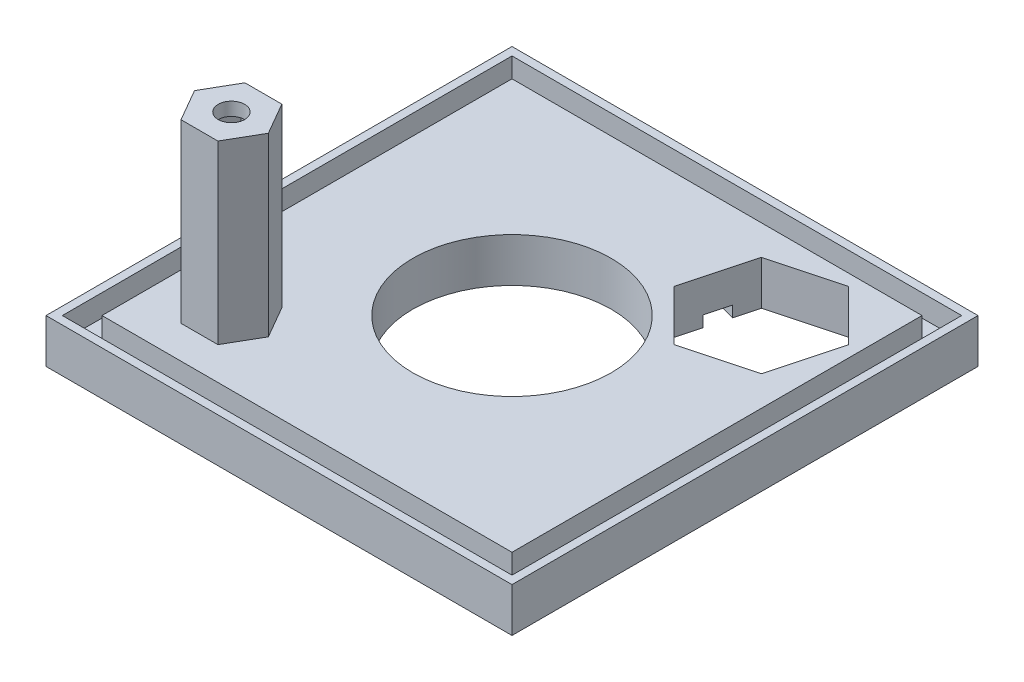
SolidWorks part; units mm, degrees
ref_plane "Front Plane" through (0, 0, 0) normal (0, 0, 1) x (1, 0, 0)
ref_plane "Top Plane" through (0, 0, 0) normal (0, 1, 0) x (1, 0, 0)
ref_plane "Right Plane" through (0, 0, 0) normal (1, 0, 0) x (0, 0, -1)
sketch "Sketch1" plane through (0, 0, 0) normal (0, 1, 0) x (1, 0, 0)
  line L1 (-52.85, -52.85) -> (52.85, -52.85)
  line L2 (-52.85, -52.85) -> (-52.85, 52.85)
  line L3 (-52.85, 52.85) -> (52.85, 52.85)
  line L4 (52.85, -52.85) -> (52.85, 52.85)
  line L5 (-52.85, -52.85) -> (52.85, 52.85) construction
  line L6 (-52.85, 52.85) -> (52.85, -52.85) construction
  line L11 (-82.2142, -82.2142) -> (73.2478, 73.2478) construction
  line L12 (-76.9859, 78.469) -> (76.9859, -78.469) construction
  circle A1 centre (0, 0) radius 22.5
  dimension "D1" = 105.7
  dimension "D2" = 45
  dimension "D3" = 105.7
extrude "Boss-Extrude1" add sketch "Sketch1" along normal blind 10
sketch "Sketch3" plane through (0, 10, 0) normal (0, 1, 0) x (1, 0, 0)
  line L1 (-51, -51) -> (51, -51)
  line L2 (-51, -51) -> (-51, 51)
  line L3 (-51, 51) -> (51, 51)
  line L4 (51, -51) -> (51, 51)
  line L5 (-51, -51) -> (51, 51) construction
  line L6 (-51, 51) -> (51, -51) construction
  line L7 (-46.5, -46.5) -> (46.5, -46.5)
  line L8 (-46.5, -46.5) -> (-46.5, 46.5)
  line L9 (-46.5, 46.5) -> (46.5, 46.5)
  line L10 (46.5, -46.5) -> (46.5, 46.5)
  line L11 (-46.5, -46.5) -> (46.5, 46.5) construction
  line L12 (-46.5, 46.5) -> (46.5, -46.5) construction
  point P0 (0, 0)
  point P2 (0, 0)
  dimension "D4" = 102
  dimension "D6" = 93
extrude "Cut-Extrude1" cut sketch "Sketch3" against normal blind 5
sketch "Sketch4" plane through (0, 10, 0) normal (0, 1, 0) x (1, 0, 0)
  line L0 (0, 0) -> (28.2843, 28.2843) construction
  line L1 (0, 0) -> (46.5, 0) construction
  line L2 (46.5, -46.5) -> (46.5, 46.5) construction
  circle A0 centre (28.2843, 28.2843) radius 10.375
  dimension "D1" = 20.75
  dimension "D2" = 40
  dimension "D3" = 45
sketch "Sketch8" plane through (0, 10, 0) normal (0, -1, 0) x (1, 0, 0)
  line L0 (0, 0) -> (-31.8198, 31.8198) construction
  line L1 (0, 0) -> (-22.5, 0) construction
  circle A0 centre (-31.8198, 31.8198) radius 3
  circle A2 centre (0, 0) radius 22.5 construction
  dimension "D1" = 6
  dimension "D2" = 45
  dimension "D3" = 45
extrude "Cut-Extrude5" cut sketch "Sketch8" along normal through all
sketch "Sketch9" plane through (0, 10, 0) normal (0, -1, 0) x (1, 0, 0)
  line L1 (-23.4482, 31.8198) -> (-27.634, 39.0698)
  line L2 (-27.634, 39.0698) -> (-36.0056, 39.0698)
  line L3 (-36.0056, 39.0698) -> (-40.1914, 31.8198)
  line L4 (-40.1914, 31.8198) -> (-36.0056, 24.5698)
  line L5 (-36.0056, 24.5698) -> (-27.634, 24.5698)
  line L6 (-27.634, 24.5698) -> (-23.4482, 31.8198)
  circle A0 centre (-31.8198, 31.8198) radius 7 construction
  circle A2 centre (-31.8198, 31.8198) radius 3 construction
  circle A3 centre (-31.8198, 31.8198) radius 3
  circle A4 centre (-31.8198, 31.8198) radius 7.25 construction
  dimension "D1" = 14
  dimension "D2" = 14.5
extrude "Cut-Extrude7" cut sketch "Sketch4" against normal through all
sketch "Sketch12" plane through (0, 0, 0) normal (0, -1, 0) x (1, 0, 0)
  line L0 (28.2843, -28.2843) -> (1.5232, -28.2843) construction
  line L1 (43.8992, -32.4683) -> (39.7152, -16.8533)
  line L2 (39.7152, -16.8533) -> (24.1003, -12.6693)
  line L3 (24.1003, -12.6693) -> (12.6693, -24.1003)
  line L4 (12.6693, -24.1003) -> (16.8533, -39.7152)
  line L5 (16.8533, -39.7152) -> (32.4683, -43.8992)
  line L6 (32.4683, -43.8992) -> (43.8992, -32.4683)
  circle A0 centre (28.2843, -28.2843) radius 14 construction
  dimension "D1" = 28
  dimension "D2" = 45
sketch "Sketch15" plane through (0, 0, 0) normal (0, -1, 0) x (1, 0, 0)
  line L1 (-25.238, 31.8198) -> (-28.5289, 37.5198)
  line L2 (-28.5289, 37.5198) -> (-35.1107, 37.5198)
  line L3 (-35.1107, 37.5198) -> (-38.4016, 31.8198)
  line L4 (-38.4016, 31.8198) -> (-35.1107, 26.1198)
  line L5 (-35.1107, 26.1198) -> (-28.5289, 26.1198)
  line L6 (-28.5289, 26.1198) -> (-25.238, 31.8198)
  circle A1 centre (-31.8198, 31.8198) radius 5.7 construction
  dimension "D1" = 11.4
extrude "Cut-Extrude11" cut sketch "Sketch12" against normal through all
extrude "Boss-Extrude5" add sketch "Sketch9" against normal blind 40
sketch "Sketch16" plane through (0, 0, 0) normal (0, -1, 0) x (1, 0, 0)
  line L1 (-25.7576, 31.8198) -> (-28.7887, 37.0698)
  line L2 (-28.7887, 37.0698) -> (-34.8509, 37.0698)
  line L3 (-34.8509, 37.0698) -> (-37.882, 31.8198)
  line L4 (-37.882, 31.8198) -> (-34.8509, 26.5698)
  line L5 (-34.8509, 26.5698) -> (-28.7887, 26.5698)
  line L6 (-28.7887, 26.5698) -> (-25.7576, 31.8198)
  circle A0 centre (-31.8198, 31.8198) radius 5.25 construction
  dimension "D1" = 10.5
extrude "Cut-Extrude12" cut sketch "Sketch16" against normal offset from surface (47 mm away) 3 up to face at (-31.8198, 50, 28.8198)
sketch "Sketch17" plane through (0, 0, 0) normal (0, -1, 0) x (1, 0, 0)
  line L0 (31.9077, -14.7613) -> (24.6608, -41.8072) construction
  line L1 (39.7152, -16.8533) -> (24.1003, -12.6693) construction
  line L2 (16.8533, -39.7152) -> (32.4683, -43.8992) construction
  line L3 (29.2514, -14.0496) -> (30.0926, -10.9103)
  line L8 (30.0926, -10.9103) -> (35.4052, -12.3338)
  line L9 (35.4052, -12.3338) -> (34.564, -15.4731)
  line L10 (34.564, -15.4731) -> (29.2514, -14.0496)
  line L11 (18.3848, -18.3848) -> (28.2843, -28.2843) construction
  line L12 (24.1003, -12.6693) -> (12.6693, -24.1003) construction
  line L13 (36.2392, -40.1283) -> (40.1283, -36.2392)
  line L14 (40.1283, -36.2392) -> (42.4264, -38.5373)
  line L15 (42.4264, -38.5373) -> (38.5373, -42.4264)
  line L16 (38.5373, -42.4264) -> (36.2392, -40.1283)
  line L17 (14.0496, -29.2514) -> (15.4731, -34.564)
  line L18 (15.4731, -34.564) -> (12.3338, -35.4052)
  line L19 (12.3338, -35.4052) -> (10.9103, -30.0926)
  line L20 (10.9103, -30.0926) -> (14.0496, -29.2514)
  point P24 (28.2843, -28.2843)
  dimension "D1" = 3.25
  dimension "D2" = 5.5
  dimension "D3" = 3
extrude "Cut-Extrude13" cut sketch "Sketch17" against normal blind 2.5
